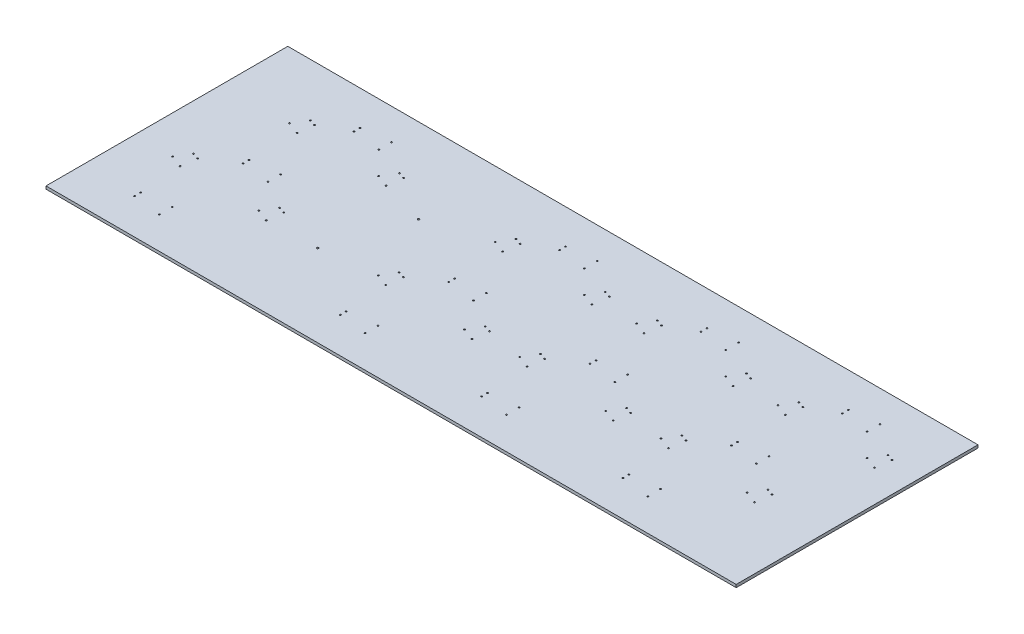
SolidWorks part; units mm, degrees
ref_plane "Спереди" through (0, 0, 0) normal (0, 0, 1) x (1, 0, 0)
ref_plane "Сверху" through (0, 0, 0) normal (0, 1, 0) x (1, 0, 0)
ref_plane "Справа" through (0, 0, 0) normal (1, 0, 0) x (0, 0, -1)
sketch "Эскиз1" plane through (0, 0, 0) normal (0, 1, 0) x (1, 0, 0)
  line L1 (-328.2688, 197.4879) -> (396.7312, 197.4879)
  line L2 (-328.2688, 197.4879) -> (-328.2688, -56.5121)
  line L3 (-328.2688, -56.5121) -> (396.7312, -56.5121)
  line L4 (396.7312, 197.4879) -> (396.7312, -56.5121)
  dimension "D1" = 725
  dimension "D2" = 254
extrude "Бобышка-Вытянуть1" add sketch "Эскиз1" along normal blind 3
sketch "Эскиз2" plane through (0, 3, 0) normal (0, 1, 0) x (1, 0, 0)
  line L0 (241.088, 45.4143) -> (229.7261, 49.2754) construction
  circle A0 centre (267.8098, 73.7123) radius 0.75
  circle A1 centre (267.8098, 67.469) radius 0.75
  circle A2 centre (297.4844, 63.8335) radius 0.75
  circle A3 centre (297.4844, 77.284) radius 0.75
  circle A4 centre (296.8817, 161.0903) radius 0.75
  circle A5 centre (296.8817, 154.847) radius 0.75
  circle A6 centre (326.5563, 151.2115) radius 0.75
  circle A7 centre (326.5563, 164.662) radius 0.75
  circle A8 centre (240.5462, -12.9777) radius 0.75
  circle A9 centre (240.5462, -19.221) radius 0.75
  circle A10 centre (270.2208, -22.8565) radius 0.75
  circle A11 centre (270.2208, -9.406) radius 0.75
  circle A12 centre (232.9356, 50.297) radius 0.75
  circle A13 centre (239.4027, 48.0994) radius 0.75
  circle A14 centre (237.2879, 31.866) radius 0.75
  circle A15 centre (224.6347, 36.6492) radius 0.75
  circle A16 centre (327.3554, 46.3011) radius 0.75
  circle A17 centre (333.8224, 44.1034) radius 0.75
  circle A18 centre (331.7077, 27.87) radius 0.75
  circle A19 centre (319.0545, 32.6533) radius 0.75
  circle A20 centre (263.9566, 142.037) radius 0.75
  circle A21 centre (270.4237, 139.8393) radius 0.75
  circle A22 centre (268.3089, 123.6059) radius 0.75
  circle A23 centre (255.6558, 128.3892) radius 0.75
  circle A24 centre (358.8783, 140.753) radius 0.75
  circle A25 centre (365.3454, 138.5553) radius 0.75
  circle A26 centre (363.2306, 122.3219) radius 0.75
  circle A27 centre (350.5775, 127.1052) radius 0.75
  circle A28 centre (119.3098, 73.7123) radius 0.75
  circle A29 centre (119.3098, 67.469) radius 0.75
  circle A30 centre (148.9844, 63.8335) radius 0.75
  circle A31 centre (148.9844, 77.284) radius 0.75
  circle A32 centre (148.3817, 161.0903) radius 0.75
  circle A33 centre (148.3817, 154.847) radius 0.75
  circle A34 centre (178.0563, 151.2115) radius 0.75
  circle A35 centre (178.0563, 164.662) radius 0.75
  circle A36 centre (92.0462, -12.9777) radius 0.75
  circle A37 centre (92.0462, -19.221) radius 0.75
  circle A38 centre (121.7208, -22.8565) radius 0.75
  circle A39 centre (121.7208, -9.406) radius 0.75
  circle A40 centre (84.4356, 50.297) radius 0.75
  circle A41 centre (90.9027, 48.0994) radius 0.75
  circle A42 centre (88.7879, 31.866) radius 0.75
  circle A43 centre (76.1347, 36.6492) radius 0.75
  circle A44 centre (178.8554, 46.3011) radius 0.75
  circle A45 centre (185.3224, 44.1034) radius 0.75
  circle A46 centre (183.2077, 27.87) radius 0.75
  circle A47 centre (170.5545, 32.6533) radius 0.75
  circle A48 centre (115.4566, 142.037) radius 0.75
  circle A49 centre (121.9237, 139.8393) radius 0.75
  circle A50 centre (119.8089, 123.6059) radius 0.75
  circle A51 centre (107.1558, 128.3892) radius 0.75
  circle A52 centre (210.3783, 140.753) radius 0.75
  circle A53 centre (216.8454, 138.5553) radius 0.75
  circle A54 centre (214.7306, 122.3219) radius 0.75
  circle A55 centre (202.0775, 127.1052) radius 0.75
  circle A56 centre (-29.1902, 73.7123) radius 0.75
  circle A57 centre (-29.1902, 67.469) radius 0.75
  circle A58 centre (0.4844, 63.8335) radius 0.75
  circle A59 centre (0.4844, 77.284) radius 0.75
  circle A60 centre (-0.1183, 161.0903) radius 0.75
  circle A61 centre (-0.1183, 154.847) radius 0.75
  circle A62 centre (29.5563, 151.2115) radius 0.75
  circle A63 centre (29.5563, 164.662) radius 0.75
  circle A64 centre (-56.4538, -12.9777) radius 0.75
  circle A65 centre (-56.4538, -19.221) radius 0.75
  circle A66 centre (-26.7792, -22.8565) radius 0.75
  circle A67 centre (-26.7792, -9.406) radius 0.75
  circle A68 centre (-64.0644, 50.297) radius 0.75
  circle A69 centre (-57.5973, 48.0994) radius 0.75
  circle A70 centre (-59.7121, 31.866) radius 0.75
  circle A71 centre (-72.3653, 36.6492) radius 0.75
  circle A72 centre (30.3554, 46.3011) radius 0.75
  circle A73 centre (36.8224, 44.1034) radius 0.75
  circle A74 centre (34.7077, 27.87) radius 0.75
  circle A75 centre (22.0545, 32.6533) radius 0.75
  circle A76 centre (-33.0434, 142.037) radius 0.75
  circle A77 centre (-26.5763, 139.8393) radius 0.75
  circle A78 centre (-28.6911, 123.6059) radius 0.75
  circle A79 centre (-41.3442, 128.3892) radius 0.75
  circle A80 centre (61.8783, 140.753) radius 0.75
  circle A81 centre (68.3454, 138.5553) radius 0.75
  circle A82 centre (66.2306, 122.3219) radius 0.75
  circle A83 centre (53.5775, 127.1052) radius 0.75
  circle A84 centre (-245.1902, 73.7123) radius 0.75
  circle A85 centre (-245.1902, 67.469) radius 0.75
  circle A86 centre (-215.5156, 63.8335) radius 0.75
  circle A87 centre (-215.5156, 77.284) radius 0.75
  circle A88 centre (-216.1183, 161.0903) radius 0.75
  circle A89 centre (-216.1183, 154.847) radius 0.75
  circle A90 centre (-186.4437, 151.2115) radius 0.75
  circle A91 centre (-186.4437, 164.662) radius 0.75
  circle A92 centre (-272.4538, -12.9777) radius 0.75
  circle A93 centre (-272.4538, -19.221) radius 0.75
  circle A94 centre (-242.7792, -22.8565) radius 0.75
  circle A95 centre (-242.7792, -9.406) radius 0.75
  circle A96 centre (-280.0644, 50.297) radius 0.75
  circle A97 centre (-273.5973, 48.0994) radius 0.75
  circle A98 centre (-275.7121, 31.866) radius 0.75
  circle A99 centre (-288.3653, 36.6492) radius 0.75
  circle A100 centre (-185.6446, 46.3011) radius 0.75
  circle A101 centre (-179.1776, 44.1034) radius 0.75
  circle A102 centre (-181.2923, 27.87) radius 0.75
  circle A103 centre (-193.9455, 32.6533) radius 0.75
  circle A104 centre (-249.0434, 142.037) radius 0.75
  circle A105 centre (-242.5763, 139.8393) radius 0.75
  circle A106 centre (-244.6911, 123.6059) radius 0.75
  circle A107 centre (-257.3442, 128.3892) radius 0.75
  circle A108 centre (-154.1217, 140.753) radius 0.75
  circle A109 centre (-147.6546, 138.5553) radius 0.75
  circle A110 centre (-149.7694, 122.3219) radius 0.75
  circle A111 centre (-162.4225, 127.1052) radius 0.75
  circle A112 centre (-102.1675, 108.7884) radius 1
  circle A113 centre (-129.096, 29.6687) radius 1
  point P230 (-129.096, 29.6687)
  point P231 (-102.1675, 108.7884)
  dimension "D1" = 1.5
  dimension "D2" = 2
  dimension "D6" = 2
  dimension "D7" = 2
  dimension "D3" = 2
  dimension "D4" = 3
  dimension "D5" = 2
extrude "Вырез-Вытянуть1" cut sketch "Эскиз2" against normal blind 10
